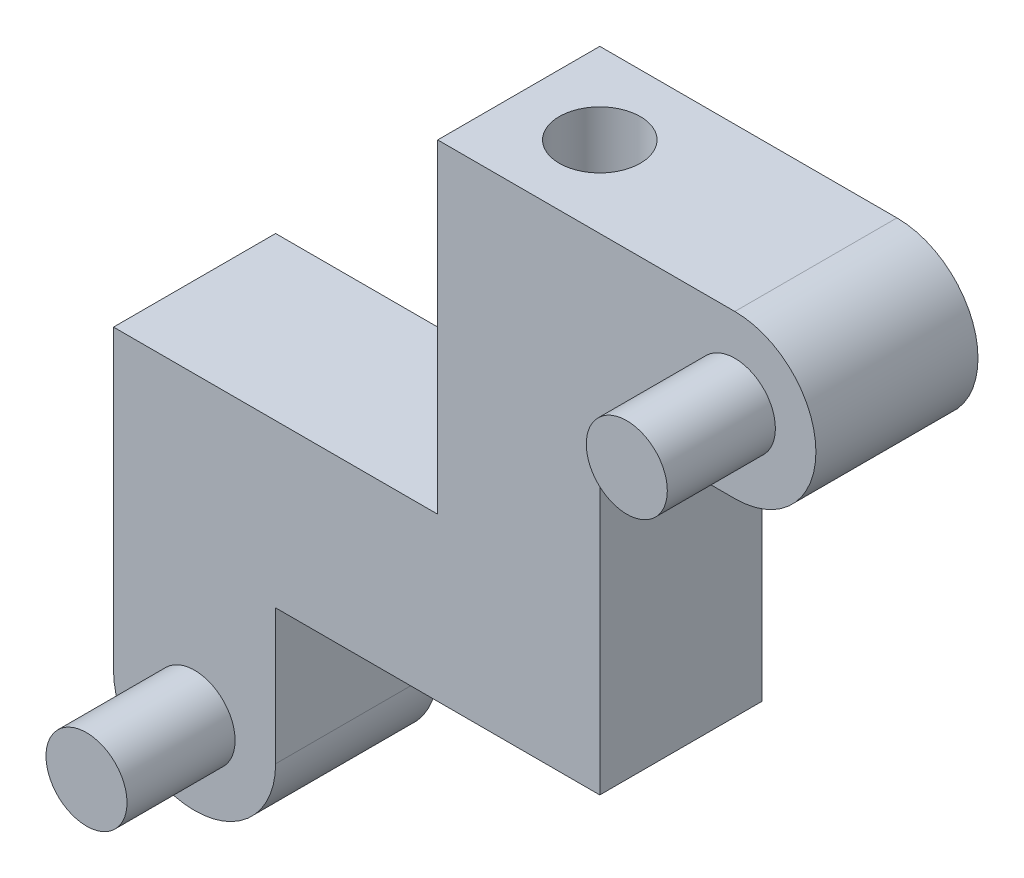
SolidWorks part; units mm, degrees
material "Nickel"
ref_plane "Front Plane" through (0, 0, 0) normal (0, 0, 1) x (1, 0, 0)
ref_plane "Top Plane" through (0, 0, 0) normal (0, 1, 0) x (1, 0, 0)
ref_plane "Right Plane" through (0, 0, 0) normal (1, 0, 0) x (0, 0, -1)
sketch "Sketch1" plane through (0, 0, 0) normal (0, 0, 1) x (1, 0, 0)
  line L0 (0, 0) -> (0, 60)
  line L1 (0, 60) -> (55, 60)
  line L2 (55, 30) -> (30, 30)
  line L3 (30, 30) -> (30, -30)
  line L4 (30, -30) -> (0, 0)
  arc A0 (55, 30) -> (55, 60) centre (55, 45) ccw
  dimension "D4" = 30
  dimension "D1" = 60
  dimension "D2" = 55
  dimension "D3" = 25
  dimension "D5" = 135
extrude "Boss-Extrude1" add sketch "Sketch1" along normal blind 30
sketch "Sketch2" plane through (0, 0, 30) normal (0, 0, 1) x (1, 0, 0)
  circle A0 centre (55, 45) radius 7.5
  arc A2 (55, 30) -> (55, 60) centre (55, 45) ccw construction
  dimension "D1" = 15
extrude "Boss-Extrude2" add sketch "Sketch2" along normal blind 20
sketch "Sketch3" plane through (0, 60, 0) normal (0, 1, 0) x (1, 0, 0)
  line L0 (0, -30) -> (0, 0) construction
  circle A0 centre (15, -15) radius 7.5
  point P4 (0, -15)
  dimension "D1" = 15
  dimension "D2" = 15
extrude "Cut-Extrude1" cut sketch "Sketch3" against normal blind 20
mirror "Mirror1" about plane through (30, -30, 30) normal (0.7071, 0.7071, 0) of "Cut-Extrude1", "Boss-Extrude2", "Boss-Extrude1"
